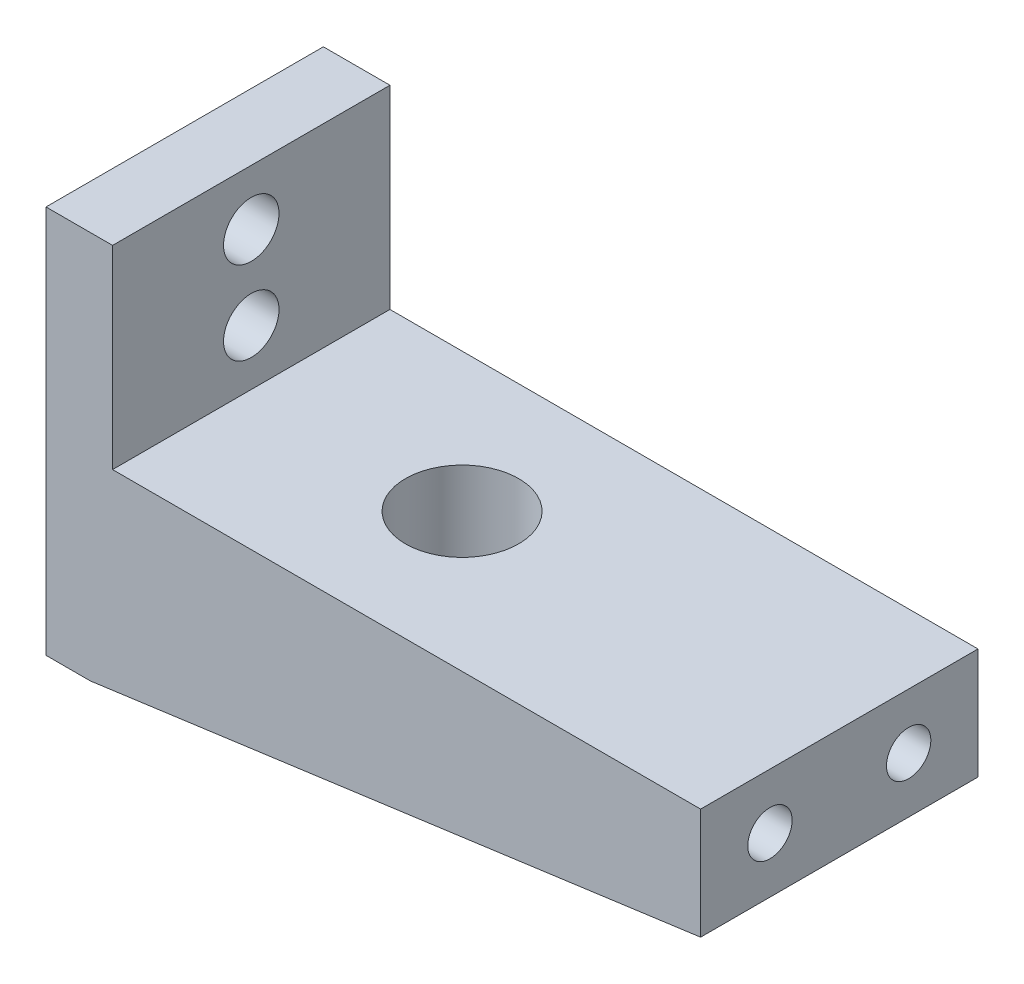
SolidWorks part; units mm, degrees
ref_plane "Alzado" through (0, 0, 0) normal (0, 0, 1) x (1, 0, 0)
ref_plane "Planta" through (0, 0, 0) normal (0, 1, 0) x (1, 0, 0)
ref_plane "Vista lateral" through (0, 0, 0) normal (1, 0, 0) x (0, 0, -1)
sketch "Croquis3" plane through (0, 0, 0) normal (1, 0, 0) x (0, 0, -1)
  line L1 (-8.1731, 20.3125) -> (16.8269, 20.3125)
  line L2 (-8.1731, 20.3125) -> (-8.1731, -14.6875)
  line L3 (-8.1731, -14.6875) -> (16.8269, -14.6875)
  line L4 (16.8269, 20.3125) -> (16.8269, -14.6875)
  dimension "D1" = 25
  dimension "D2" = 35
extrude "Saliente-Extruir2" add sketch "Croquis3" along normal blind 4
sketch "Croquis5" plane through (4, 0, 0) normal (1, 0, 0) x (0, 0, -1)
  line L0 (16.8269, -14.6875) -> (16.8269, 20.3125) construction
  line L1 (-8.1731, 20.3125) -> (16.8269, 20.3125)
  line L2 (-8.1731, 20.3125) -> (-8.1731, 2.8125)
  line L3 (-8.1731, 2.8125) -> (16.8269, 2.8125)
  line L4 (16.8269, 20.3125) -> (16.8269, 2.8125)
extrude "Saliente-Extruir3" add sketch "Croquis5" along normal blind 2
sketch "Croquis7" plane through (4, 0, 0) normal (1, 0, 0) x (0, 0, -1)
  line L0 (16.8269, -14.6875) -> (16.8269, 2.8125) construction
  line L1 (-8.1731, 2.8125) -> (16.8269, 2.8125)
  line L2 (-8.1731, 2.8125) -> (-8.1731, -7.1875)
  line L3 (-8.1731, -7.1875) -> (16.8269, -7.1875)
  line L4 (16.8269, 2.8125) -> (16.8269, -7.1875)
  dimension "D1" = 10
extrude "Saliente-Extruir5" add sketch "Croquis7" along normal blind 55
sketch "Croquis8" plane through (6, 0, 0) normal (1, 0, 0) x (0, 0, -1)
  line L0 (16.8269, 20.3125) -> (-8.1731, 20.3125) construction
  circle A0 centre (4.3269, 15.3125) radius 2.5
  circle A1 centre (4.3269, 7.8125) radius 2.5
  dimension "D1" = 5
  dimension "D2" = 5
  dimension "D3" = 7.5
  dimension "D4" = 5
extrude "Cortar-Extruir1" cut sketch "Croquis8" against normal blind 55
sketch "Croquis9" plane through (0, 2.8125, 0) normal (0, 1, 0) x (1, 0, 0)
  line L9 (0, 16.8269) -> (0, -8.1731) construction
  circle A1 centre (25, 4.3269) radius 5.1
  dimension "D3" = 10.2
  dimension "D2" = 25
sketch "Croquis10" plane through (0, 0, 8.1731) normal (0, 0, 1) x (1, 0, 0)
  line L0 (4, -14.6875) -> (59, -7.1875)
  line L1 (59, -7.1875) -> (4, -7.1875)
  line L2 (4, -7.1875) -> (4, -14.6875)
extrude "Saliente-Extruir6" add sketch "Croquis10" against normal through all
extrude "Cortar-Extruir3" cut sketch "Croquis9" against normal blind 4
sketch "Croquis11" plane through (59, 0, 0) normal (1, 0, 0) x (0, 0, -1)
  line L2 (16.8269, -7.1875) -> (16.8269, 2.8125) construction
  line L6 (-8.1731, 2.8125) -> (16.8269, 2.8125) construction
  circle A0 centre (-1.9231, -2.1875) radius 2
  circle A1 centre (10.5769, -2.1875) radius 2
  dimension "D1" = 4
  dimension "D2" = 4
  dimension "D3" = 12.5
  dimension "D4" = 6.25
  dimension "D5" = 5
extrude "Cortar-Extruir4" cut sketch "Croquis11" against normal blind 20
sketch "Croquis12" plane through (0, -1.1875, 0) normal (0, 1, 0) x (1, 0, 0)
  line L7 (0, 16.8269) -> (0, -8.1731) construction
  circle A1 centre (25, 4.3269) radius 5.1
  dimension "D2" = 25
extrude "Cortar-Extruir5" cut sketch "Croquis12" against normal blind 45
